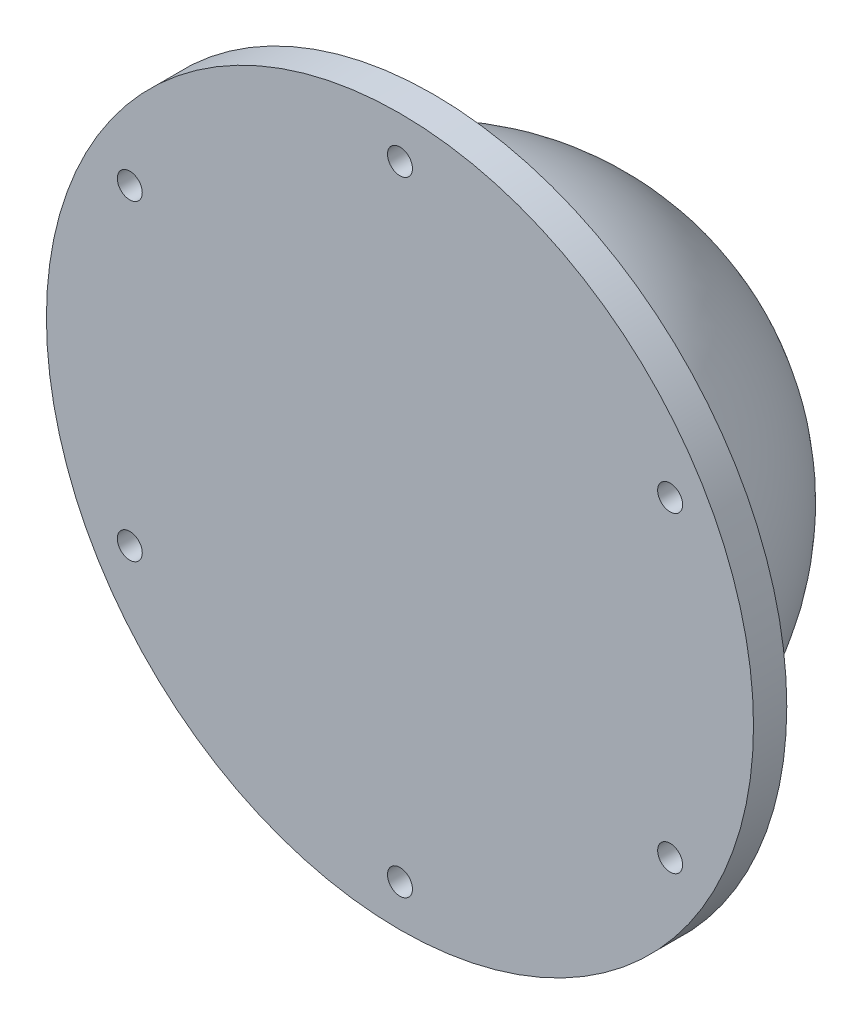
SolidWorks part; units mm, degrees
ref_plane "前视基准面" through (0, 0, 0) normal (0, 0, 1) x (1, 0, 0)
ref_plane "上视基准面" through (0, 0, 0) normal (0, 1, 0) x (1, 0, 0)
ref_plane "右视基准面" through (0, 0, 0) normal (1, 0, 0) x (0, 0, -1)
sketch "草图1" plane through (0, 0, 0) normal (0, 0, 1) x (1, 0, 0)
  circle A0 centre (0, 0) radius 85
  circle A1 centre (0, 0) radius 60 construction
  circle A2 centre (0, 0) radius 75 construction
  circle A3 centre (0, 75) radius 3
  circle A4 centre (64.9519, 37.5) radius 3
  circle A5 centre (64.9519, -37.5) radius 3
  circle A6 centre (0, -75) radius 3
  circle A7 centre (-64.9519, -37.5) radius 3
  circle A8 centre (-64.9519, 37.5) radius 3
  point P19 (0, 0)
  dimension "D1" = 170
  dimension "D2" = 120
  dimension "D3" = 6
  dimension "D4" = 150
  dimension "D5" = 6
extrude "凸台-拉伸1" add sketch "草图1" along normal blind 8
sketch "草图2" plane through (0, 0, 0) normal (0, 1, 0) x (1, 0, 0)
  line L0 (-60, 0) -> (-65, 0)
  line L1 (0, 60) -> (0, 65)
  arc A0 (0, 65) -> (-65, 0) centre (0, 0) ccw
  arc A1 (0, 60) -> (-60, 0) centre (0, 0) ccw
  dimension "D1" = 130
  dimension "D2" = 120
revolve "旋转1" add sketch "草图2" angle 360 about L1
